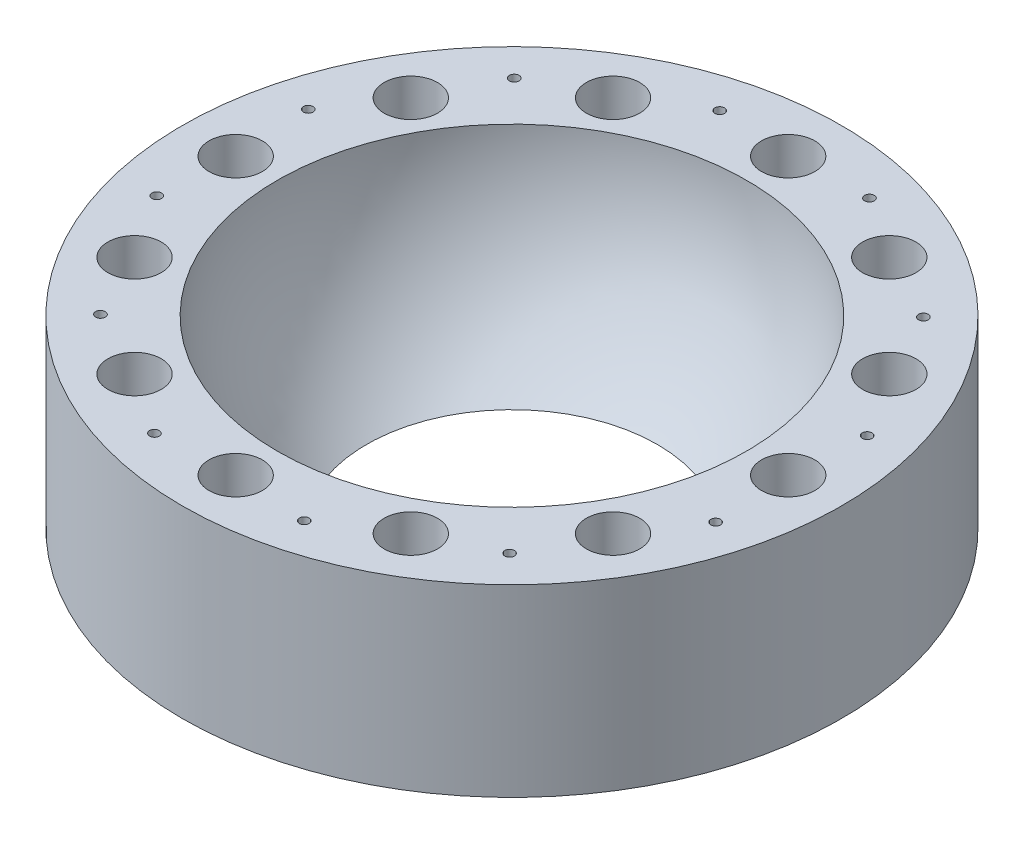
SolidWorks part; units mm, degrees
ref_plane "前视基准面" through (0, 0, 0) normal (0, 0, 1) x (1, 0, 0)
ref_plane "上视基准面" through (0, 0, 0) normal (0, 1, 0) x (1, 0, 0)
ref_plane "右视基准面" through (0, 0, 0) normal (1, 0, 0) x (0, 0, -1)
other "Configuration Table"
sketch "草图1" plane through (0, 0, 0) normal (0, 1, 0) x (1, 0, 0)
  circle A0 centre (0, 0) radius 68
  circle A2 centre (0, 57) radius 5.5
  circle A3 centre (28.5, 49.3634) radius 5.5
  circle A4 centre (49.3634, 28.5) radius 5.5
  circle A5 centre (57, 0) radius 5.5
  circle A6 centre (49.3634, -28.5) radius 5.5
  circle A7 centre (28.5, -49.3634) radius 5.5
  circle A8 centre (0, -57) radius 5.5
  circle A9 centre (-28.5, -49.3634) radius 5.5
  circle A10 centre (-49.3634, -28.5) radius 5.5
  circle A11 centre (-57, 0) radius 5.5
  circle A12 centre (-49.3634, 28.5) radius 5.5
  circle A13 centre (-28.5, 49.3634) radius 5.5
  point P30 (0, 0)
  dimension "D1" = 12
extrude "凸台-拉伸1" add sketch "草图1" along normal blind 60
sketch "草图2" plane through (0, 60, 0) normal (0, 1, 0) x (1, 0, 0)
  circle A0 centre (0, 57) radius 8.75
  circle A1 centre (49.3634, 28.5) radius 8.75
  circle A2 centre (49.3634, -28.5) radius 8.75
  circle A3 centre (0, -57) radius 8.75
  circle A4 centre (-49.3634, -28.5) radius 8.75
  circle A5 centre (-49.3634, 28.5) radius 8.75
  point P15 (0, 0)
  dimension "D1" = 6
extrude "切除-拉伸1" cut sketch "草图2" against normal blind 10.8
sketch "草图4" plane through (0, 0, 0) normal (0, -1, 0) x (1, 0, 0)
  circle A0 centre (28.5, 49.3634) radius 8.75
  circle A1 centre (57, 0) radius 8.75
  circle A2 centre (28.5, -49.3634) radius 8.75
  circle A3 centre (-28.5, -49.3634) radius 8.75
  circle A4 centre (-57, 0) radius 8.75
  circle A5 centre (-28.5, 49.3634) radius 8.75
  point P16 (0, 0)
  dimension "D1" = 6
extrude "切除-拉伸2" cut sketch "草图4" against normal blind 10.8
sketch "草图6" plane through (0, 60, 0) normal (0, 1, 0) x (1, 0, 0)
  circle A0 centre (0, 0) radius 68
extrude "切除-拉伸6" cut sketch "草图6" against normal blind 22
sketch "草图8" plane through (0, 0, 0) normal (0, 0, 1) x (1, 0, 0)
  line L1 (0, 0) -> (0, 38)
  line L3 (0, -10.4149) -> (0, 86.4149)
  arc A0 (0, -10.4149) -> (0, 86.4149) centre (0, 38) ccw
revolve "切除-旋转3" cut sketch "草图8" angle 360 about L3
sketch "草图9" plane through (0, 0, 0) normal (0, -1, 0) x (1, 0, 0)
  circle A1 centre (15.2104, 58.0753) radius 1
  circle A2 centre (42.2102, 42.6895) radius 1
  circle A3 centre (57.8999, 15.8651) radius 1
  circle A4 centre (58.0753, -15.2104) radius 1
  circle A5 centre (42.6895, -42.2102) radius 1
  circle A6 centre (15.8651, -57.8999) radius 1
  circle A7 centre (-15.2104, -58.0753) radius 1
  circle A8 centre (-42.2102, -42.6895) radius 1
  circle A9 centre (-57.8999, -15.8651) radius 1
  circle A10 centre (-58.0753, 15.2104) radius 1
  circle A11 centre (-42.6895, 42.2102) radius 1
  circle A12 centre (-15.8651, 57.8999) radius 1
  point P28 (0, 0)
  dimension "D1" = 12
extrude "切除-拉伸7" cut sketch "草图9" against normal through all
